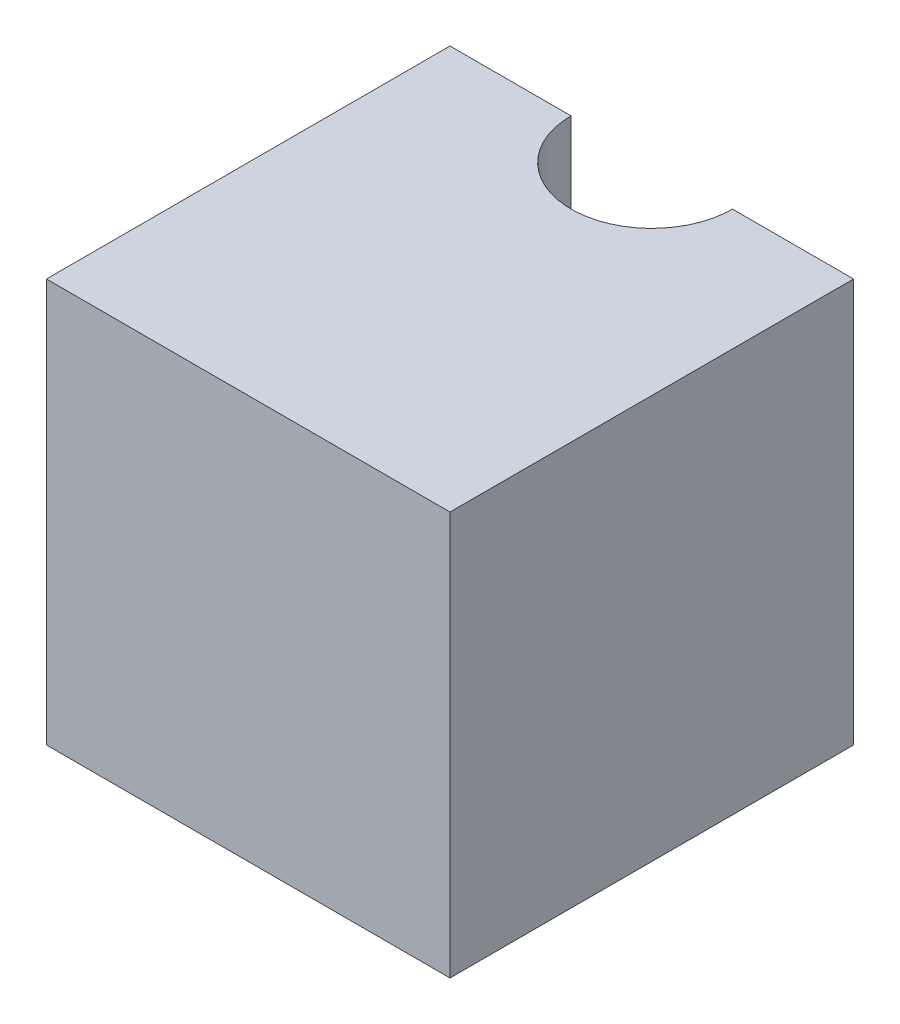
SolidWorks part; units mm, degrees
ref_plane "前视基准面" through (0, 0, 0) normal (0, 0, 1) x (1, 0, 0)
ref_plane "上视基准面" through (0, 0, 0) normal (0, 1, 0) x (1, 0, 0)
ref_plane "右视基准面" through (0, 0, 0) normal (1, 0, 0) x (0, 0, -1)
other "Configuration Table"
sketch "草图1" plane through (0, 0, 0) normal (0, 0, 1) x (1, 0, 0)
  line L1 (-50, -50) -> (50, -50)
  line L2 (-50, -50) -> (-50, 50)
  line L3 (-50, 50) -> (50, 50)
  line L4 (50, -50) -> (50, 50)
  line L5 (-50, -50) -> (50, 50) construction
  line L6 (-50, 50) -> (50, -50) construction
  point P0 (0, 0)
extrude "凸台-拉伸1" add sketch "草图1" along normal blind 100
sketch "草图2" plane through (0, 50, 0) normal (0, 1, 0) x (1, 0, 0)
  circle A0 centre (0, 0) radius 20
extrude "切除-拉伸1" cut sketch "草图2" against normal through all
